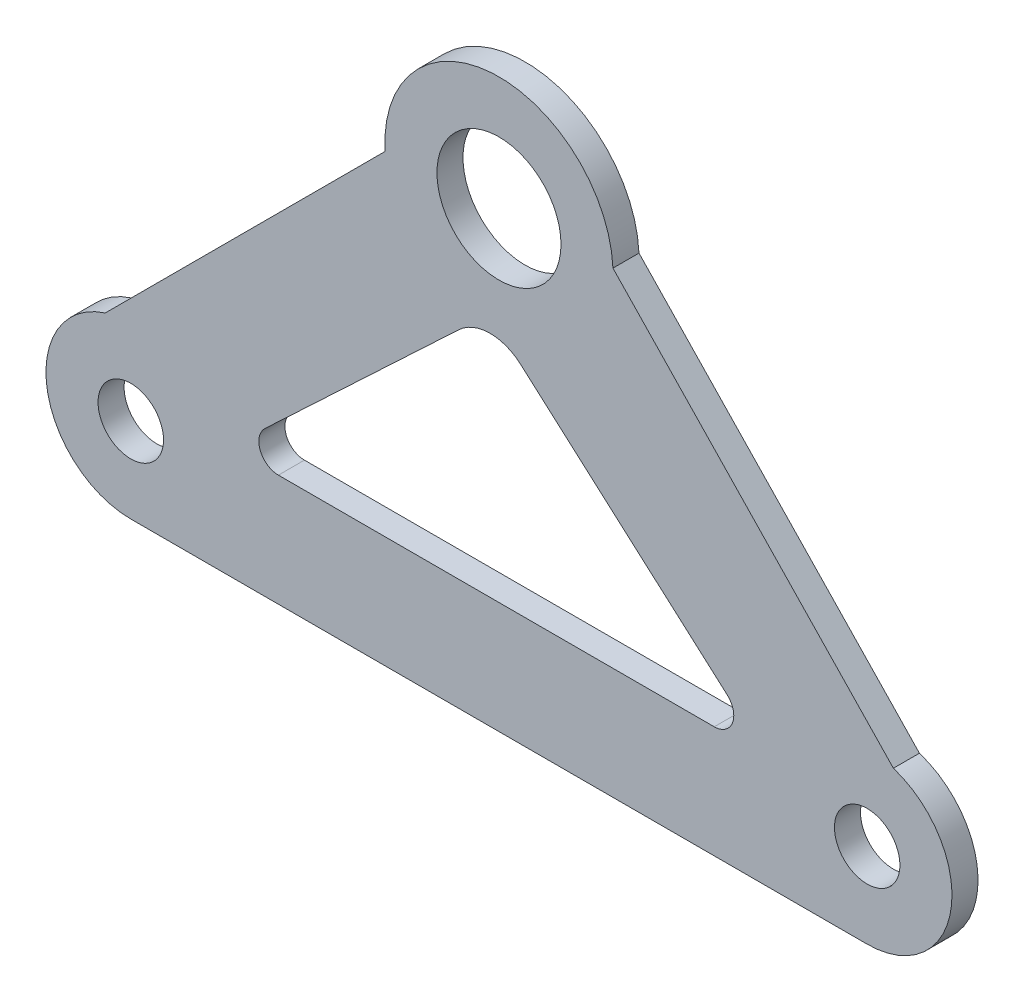
SolidWorks part; units mm, degrees
ref_plane "前视基准面" through (0, 0, 0) normal (0, 0, 1) x (1, 0, 0)
ref_plane "上视基准面" through (0, 0, 0) normal (0, 1, 0) x (1, 0, 0)
ref_plane "右视基准面" through (0, 0, 0) normal (1, 0, 0) x (0, 0, -1)
sketch "草图1" plane through (0, 0, 0) normal (0, 0, 1) x (1, 0, 0)
  line L0 (0, 0) -> (-56.5685, -56.5685) construction
  line L1 (-56.5685, -56.5685) -> (56.5685, -56.5685) construction
  line L2 (56.5685, -56.5685) -> (0, 0) construction
  line L3 (-56.5685, -51.5385) -> (-8.7668, -3.7368) construction
  line L4 (56.5685, -51.5385) -> (9.2834, -2.1539)
  line L5 (-56.5685, -61.5985) -> (56.5685, -61.5985) construction
  line L6 (-60.4847, -44.141) -> (-17.4923, -1.1486)
  line L7 (60.5951, -44.1763) -> (17.5108, 0.821)
  line L8 (-56.5685, -69.5985) -> (56.5685, -69.5985)
  circle A0 centre (0, 0) radius 9.53
  circle A1 centre (-56.5685, -56.5685) radius 5.03
  circle A2 centre (56.5685, -56.5685) radius 5.03
  arc A3 (-8.7668, -3.7368) -> (9.2834, -2.1539) centre (0, 0) cw construction
  arc A4 (-56.5685, -51.5385) -> (-56.5685, -61.5985) centre (-56.5685, -56.5685) ccw construction
  arc A5 (56.5685, -61.5985) -> (56.5685, -51.5385) centre (56.5685, -56.5685) ccw construction
  arc A6 (-17.4923, -1.1486) -> (17.5108, 0.821) centre (0, 0) cw
  arc A7 (56.5685, -69.5985) -> (60.5951, -44.1763) centre (56.5685, -56.5685) ccw
  arc A8 (-60.4847, -44.141) -> (-56.5685, -69.5985) centre (-56.5685, -56.5685) ccw
  dimension "D3" = 19.06
  dimension "D4" = 10.06
  dimension "D1" = 80
  dimension "D2" = 45
  dimension "D5" = 8
extrude "凸台-拉伸1" add sketch "草图1" along normal blind 4
sketch "草图2" plane through (0, 0, 4) normal (0, 0, 1) x (1, 0, 0)
  line L0 (-51.5407, -56.4213) -> (-1.5754, -9.3989) construction
  line L1 (-1.5754, -9.3989) -> (51.5407, -56.4213) construction
  line L2 (51.5407, -56.4213) -> (-51.5407, -56.4213) construction
  line L3 (-35.9446, -47.2366) -> (-6.1461, -19.1931)
  line L4 (3.2912, -19.0494) -> (35.0617, -47.175)
  line L5 (33.0731, -52.4213) -> (-33.8886, -52.4213)
  line L6 (-1.493, -14.8141) -> (40.9878, -52.4213) construction
  line L7 (40.9878, -52.4213) -> (-41.4538, -52.4213) construction
  line L8 (-41.4538, -52.4213) -> (-1.493, -14.8141) construction
  circle A0 centre (-56.5685, -56.5685) radius 5.03 construction
  circle A1 centre (0, 0) radius 9.53 construction
  circle A2 centre (56.5685, -56.5685) radius 5.03 construction
  arc A3 (35.0617, -47.175) -> (33.0731, -52.4213) centre (33.0731, -49.4213) cw
  arc A4 (-33.8886, -52.4213) -> (-35.9446, -47.2366) centre (-33.8886, -49.4213) cw
  arc A5 (3.2912, -19.0494) -> (-6.1461, -19.1931) centre (-1.3487, -24.2907) ccw
  point P21 (51.5407, -56.4213)
  dimension "D2" = 3
  dimension "D3" = 7
  dimension "D1" = 4
extrude "切除-拉伸1" cut sketch "草图2" against normal blind 10
